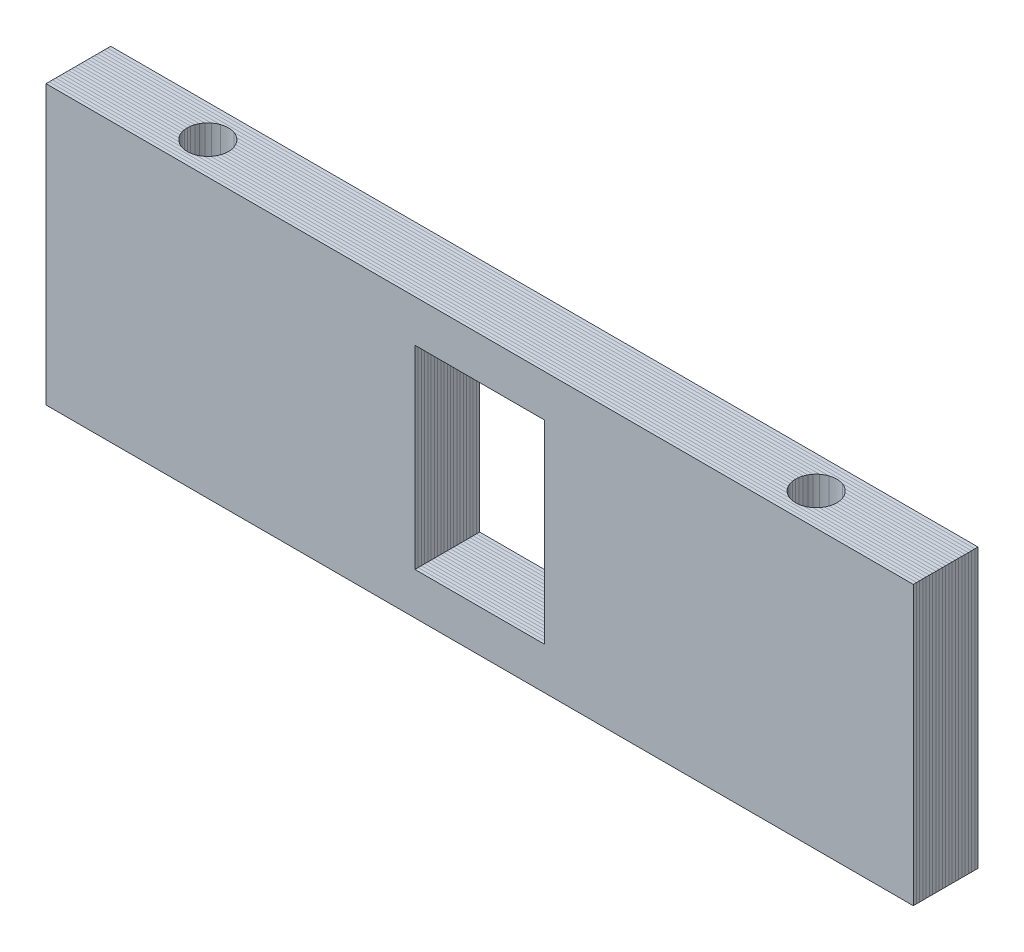
SolidWorks part; units mm, degrees
material "AISI 304"
ref_plane "Plano frontal" through (0, 0, 0) normal (0, 0, 1) x (1, 0, 0)
ref_plane "Plano superior" through (0, 0, 0) normal (0, 1, 0) x (1, 0, 0)
ref_plane "Plano direito" through (0, 0, 0) normal (1, 0, 0) x (0, 0, -1)
sketch "Esboço1" plane through (0, 0, 0) normal (0, 0, 1) x (1, 0, 0)
  line L1 (0, 0) -> (-134, 0)
  line L2 (0, 0) -> (0, 43)
  line L3 (0, 43) -> (-134, 43)
  line L4 (-134, 0) -> (-134, 43)
  line L5 (-77, 36.5) -> (-57, 36.5)
  line L6 (-77, 36.5) -> (-77, 6.5)
  line L7 (-77, 6.5) -> (-57, 6.5)
  line L8 (-57, 36.5) -> (-57, 6.5)
  dimension "D1" = 43
  dimension "D2" = 134
  dimension "D3" = 30
  dimension "D4" = 20
  dimension "D5" = 6.5
  dimension "D6" = 57
extrude "Ressalto-extrusão1" add sketch "Esboço1" along normal blind 0.5
sketch "Esboço2" plane through (0, 0, 0.5) normal (0, 0, 1) x (1, 0, 0)
  line L1 (-134, 43) -> (0, 43)
  line L2 (-134, 43) -> (-134, 0)
  line L3 (-134, 0) -> (0, 0)
  line L4 (0, 43) -> (0, 0)
  line L5 (-77, 36.5) -> (-57, 36.5)
  line L6 (-77, 36.5) -> (-77, 6.5)
  line L7 (-77, 6.5) -> (-57, 6.5)
  line L8 (-57, 36.5) -> (-57, 6.5)
extrude "Ressalto-extrusão9" add sketch "Esboço2" along normal blind 0.5 separate body
sketch "Esboço7" plane through (0, 0, 1) normal (0, 0, 1) x (1, 0, 0)
  line L1 (-134, 43) -> (0, 43)
  line L2 (-134, 43) -> (-134, 0)
  line L3 (-134, 0) -> (0, 0)
  line L4 (0, 43) -> (0, 0)
  line L5 (-57, 6.5) -> (-77, 6.5)
  line L6 (-57, 6.5) -> (-57, 36.5)
  line L7 (-57, 36.5) -> (-77, 36.5)
  line L8 (-77, 6.5) -> (-77, 36.5)
extrude "Ressalto-extrusão10" add sketch "Esboço7" along normal blind 0.5 separate body
sketch "Esboço8" plane through (0, 0, 1.5) normal (0, 0, 1) x (1, 0, 0)
  line L1 (-134, 43) -> (0, 43)
  line L2 (-134, 43) -> (-134, 0)
  line L3 (-134, 0) -> (0, 0)
  line L4 (0, 43) -> (0, 0)
  line L5 (-57, 6.5) -> (-77, 6.5)
  line L6 (-57, 6.5) -> (-57, 36.5)
  line L7 (-57, 36.5) -> (-77, 36.5)
  line L8 (-77, 6.5) -> (-77, 36.5)
extrude "Ressalto-extrusão11" add sketch "Esboço8" along normal blind 0.5 separate body
sketch "Esboço9" plane through (0, 0, 2) normal (0, 0, 1) x (1, 0, 0)
  line L1 (-134, 43) -> (0, 43)
  line L2 (-134, 43) -> (-134, 0)
  line L3 (-134, 0) -> (0, 0)
  line L4 (0, 43) -> (0, 0)
  line L5 (-77, 36.5) -> (-57, 36.5)
  line L6 (-77, 36.5) -> (-77, 6.5)
  line L7 (-77, 6.5) -> (-57, 6.5)
  line L8 (-57, 36.5) -> (-57, 6.5)
extrude "Ressalto-extrusão12" add sketch "Esboço9" along normal blind 0.5 separate body
sketch "Esboço10" plane through (0, 0, 2.5) normal (0, 0, 1) x (1, 0, 0)
  line L1 (-134, 43) -> (0, 43)
  line L2 (-134, 43) -> (-134, 0)
  line L3 (-134, 0) -> (0, 0)
  line L4 (0, 43) -> (0, 0)
  line L5 (-57, 6.5) -> (-77, 6.5)
  line L6 (-57, 6.5) -> (-57, 36.5)
  line L7 (-57, 36.5) -> (-77, 36.5)
  line L8 (-77, 6.5) -> (-77, 36.5)
extrude "Ressalto-extrusão13" add sketch "Esboço10" along normal blind 0.5 separate body
sketch "Esboço11" plane through (0, 0, 3) normal (0, 0, 1) x (1, 0, 0)
  line L1 (-134, 43) -> (0, 43)
  line L2 (-134, 43) -> (-134, 0)
  line L3 (-134, 0) -> (0, 0)
  line L4 (0, 43) -> (0, 0)
  line L5 (-57, 6.5) -> (-77, 6.5)
  line L6 (-57, 6.5) -> (-57, 36.5)
  line L7 (-57, 36.5) -> (-77, 36.5)
  line L8 (-77, 6.5) -> (-77, 36.5)
extrude "Ressalto-extrusão14" add sketch "Esboço11" along normal blind 0.5 separate body
sketch "Esboço12" plane through (0, 0, 3.5) normal (0, 0, 1) x (1, 0, 0)
  line L1 (-134, 43) -> (0, 43)
  line L2 (-134, 43) -> (-134, 0)
  line L3 (-134, 0) -> (0, 0)
  line L4 (0, 43) -> (0, 0)
  line L5 (-57, 6.5) -> (-77, 6.5)
  line L6 (-57, 6.5) -> (-57, 36.5)
  line L7 (-57, 36.5) -> (-77, 36.5)
  line L8 (-77, 6.5) -> (-77, 36.5)
extrude "Ressalto-extrusão15" add sketch "Esboço12" along normal blind 0.5 separate body
sketch "Esboço13" plane through (0, 0, 4) normal (0, 0, 1) x (1, 0, 0)
  line L1 (-134, 43) -> (0, 43)
  line L2 (-134, 43) -> (-134, 0)
  line L3 (-134, 0) -> (0, 0)
  line L4 (0, 43) -> (0, 0)
  line L5 (-57, 6.5) -> (-77, 6.5)
  line L6 (-57, 6.5) -> (-57, 36.5)
  line L7 (-57, 36.5) -> (-77, 36.5)
  line L8 (-77, 6.5) -> (-77, 36.5)
extrude "Ressalto-extrusão16" add sketch "Esboço13" along normal blind 0.5 separate body
sketch "Esboço14" plane through (0, 0, 4.5) normal (0, 0, 1) x (1, 0, 0)
  line L1 (-134, 43) -> (0, 43)
  line L2 (-134, 43) -> (-134, 0)
  line L3 (-134, 0) -> (0, 0)
  line L4 (0, 43) -> (0, 0)
  line L5 (-77, 36.5) -> (-57, 36.5)
  line L6 (-77, 36.5) -> (-77, 6.5)
  line L7 (-77, 6.5) -> (-57, 6.5)
  line L8 (-57, 36.5) -> (-57, 6.5)
extrude "Ressalto-extrusão17" add sketch "Esboço14" along normal blind 0.5 separate body
sketch "Esboço15" plane through (0, 0, 5) normal (0, 0, 1) x (1, 0, 0)
  line L1 (-134, 43) -> (0, 43)
  line L2 (-134, 43) -> (-134, 0)
  line L3 (-134, 0) -> (0, 0)
  line L4 (0, 43) -> (0, 0)
  line L5 (-57, 6.5) -> (-77, 6.5)
  line L6 (-57, 6.5) -> (-57, 36.5)
  line L7 (-57, 36.5) -> (-77, 36.5)
  line L8 (-77, 6.5) -> (-77, 36.5)
extrude "Ressalto-extrusão18" add sketch "Esboço15" along normal blind 0.5 separate body
sketch "Esboço16" plane through (0, 0, 5.5) normal (0, 0, 1) x (1, 0, 0)
  line L1 (-134, 43) -> (0, 43)
  line L2 (-134, 43) -> (-134, 0)
  line L3 (-134, 0) -> (0, 0)
  line L4 (0, 43) -> (0, 0)
  line L5 (-57, 6.5) -> (-77, 6.5)
  line L6 (-57, 6.5) -> (-57, 36.5)
  line L7 (-57, 36.5) -> (-77, 36.5)
  line L8 (-77, 6.5) -> (-77, 36.5)
extrude "Ressalto-extrusão19" add sketch "Esboço16" along normal blind 0.5 separate body
sketch "Esboço17" plane through (0, 0, 6) normal (0, 0, 1) x (1, 0, 0)
  line L1 (-134, 43) -> (0, 43)
  line L2 (-134, 43) -> (-134, 0)
  line L3 (-134, 0) -> (0, 0)
  line L4 (0, 43) -> (0, 0)
  line L5 (-77, 36.5) -> (-57, 36.5)
  line L6 (-77, 36.5) -> (-77, 6.5)
  line L7 (-77, 6.5) -> (-57, 6.5)
  line L8 (-57, 36.5) -> (-57, 6.5)
extrude "Ressalto-extrusão20" add sketch "Esboço17" along normal blind 0.5 separate body
sketch "Esboço18" plane through (0, 0, 6.5) normal (0, 0, 1) x (1, 0, 0)
  line L1 (-134, 43) -> (0, 43)
  line L2 (-134, 43) -> (-134, 0)
  line L3 (-134, 0) -> (0, 0)
  line L4 (0, 43) -> (0, 0)
  line L5 (-77, 36.5) -> (-57, 36.5)
  line L6 (-77, 36.5) -> (-77, 6.5)
  line L7 (-77, 6.5) -> (-57, 6.5)
  line L8 (-57, 36.5) -> (-57, 6.5)
extrude "Ressalto-extrusão21" add sketch "Esboço18" along normal blind 0.5 separate body
sketch "Esboço19" plane through (0, 0, 7) normal (0, 0, 1) x (1, 0, 0)
  line L1 (-134, 43) -> (0, 43)
  line L2 (-134, 43) -> (-134, 0)
  line L3 (-134, 0) -> (0, 0)
  line L4 (0, 43) -> (0, 0)
  line L5 (-77, 36.5) -> (-57, 36.5)
  line L6 (-77, 36.5) -> (-77, 6.5)
  line L7 (-77, 6.5) -> (-57, 6.5)
  line L8 (-57, 36.5) -> (-57, 6.5)
extrude "Ressalto-extrusão22" add sketch "Esboço19" along normal blind 0.5 separate body
sketch "Esboço20" plane through (0, 0, 7.5) normal (0, 0, 1) x (1, 0, 0)
  line L1 (-134, 43) -> (0, 43)
  line L2 (-134, 43) -> (-134, 0)
  line L3 (-134, 0) -> (0, 0)
  line L4 (0, 43) -> (0, 0)
  line L5 (-57, 6.5) -> (-77, 6.5)
  line L6 (-57, 6.5) -> (-57, 36.5)
  line L7 (-57, 36.5) -> (-77, 36.5)
  line L8 (-77, 6.5) -> (-77, 36.5)
extrude "Ressalto-extrusão23" add sketch "Esboço20" along normal blind 0.5 separate body
sketch "Esboço21" plane through (0, 0, 8) normal (0, 0, 1) x (1, 0, 0)
  line L1 (-134, 43) -> (0, 43)
  line L2 (-134, 43) -> (-134, 0)
  line L3 (-134, 0) -> (0, 0)
  line L4 (0, 43) -> (0, 0)
  line L5 (-77, 36.5) -> (-57, 36.5)
  line L6 (-77, 36.5) -> (-77, 6.5)
  line L7 (-77, 6.5) -> (-57, 6.5)
  line L8 (-57, 36.5) -> (-57, 6.5)
extrude "Ressalto-extrusão24" add sketch "Esboço21" along normal blind 0.5 separate body
sketch "Esboço22" plane through (0, 0, 8.5) normal (0, 0, 1) x (1, 0, 0)
  line L1 (-134, 43) -> (0, 43)
  line L2 (-134, 43) -> (-134, 0)
  line L3 (-134, 0) -> (0, 0)
  line L4 (0, 43) -> (0, 0)
  line L5 (-77, 36.5) -> (-57, 36.5)
  line L6 (-77, 36.5) -> (-77, 6.5)
  line L7 (-77, 6.5) -> (-57, 6.5)
  line L8 (-57, 36.5) -> (-57, 6.5)
extrude "Ressalto-extrusão25" add sketch "Esboço22" along normal blind 0.5 separate body
sketch "Esboço23" plane through (0, 0, 9) normal (0, 0, 1) x (1, 0, 0)
  line L1 (-134, 43) -> (0, 43)
  line L2 (-134, 43) -> (-134, 0)
  line L3 (-134, 0) -> (0, 0)
  line L4 (0, 43) -> (0, 0)
  line L5 (-57, 6.5) -> (-77, 6.5)
  line L6 (-57, 6.5) -> (-57, 36.5)
  line L7 (-57, 36.5) -> (-77, 36.5)
  line L8 (-77, 6.5) -> (-77, 36.5)
extrude "Ressalto-extrusão26" add sketch "Esboço23" along normal blind 0.5 separate body
sketch "Esboço24" plane through (0, 0, 9.5) normal (0, 0, 1) x (1, 0, 0)
  line L1 (-134, 43) -> (0, 43)
  line L2 (-134, 43) -> (-134, 0)
  line L3 (-134, 0) -> (0, 0)
  line L4 (0, 43) -> (0, 0)
  line L5 (-77, 36.5) -> (-57, 36.5)
  line L6 (-77, 36.5) -> (-77, 6.5)
  line L7 (-77, 6.5) -> (-57, 6.5)
  line L8 (-57, 36.5) -> (-57, 6.5)
extrude "Ressalto-extrusão27" add sketch "Esboço24" along normal blind 0.5 separate body
hole_wizard "Broca de rosquear para tarraxa de M3x0.51" positions "Esboço25" profile "Esboço27" hole size "M3x0.5" standard "Ansi Metric"
sketch "Esboço25" plane through (0, 43, 0) normal (0, 1, 0) x (1, 0, 0)
  line L0 (-134, -5) -> (-134, -4.5) construction
  line L1 (0, -10) -> (-134, -10) construction
  point P0 (-114, -5)
  point P2 (-20, -5)
  dimension "D1" = 20
  dimension "D2" = 5
  dimension "D3" = 20
  dimension "D4" = 5
sketch "Esboço27" plane through (-114, 43, 5) normal (1, 0, 0) x (0, 0, 1)
  line L0 (0, 0) -> (0, 25.4)
  line L1 (0, 25.4) -> (3.175, 23.4923)
  line L2 (3.175, 23.4923) -> (3.175, 0)
  line L5 (3.175, 0) -> (0, 0)
  line L10 (0, 25.4) -> (-3.175, 23.4923) construction
  line L11 (0, -6.35) -> (0, 107.95) construction
  dimension "Hole Dia." = 6.35
  dimension "Hole Depth" = 25.4
  dimension "Drill Angle" = 118
